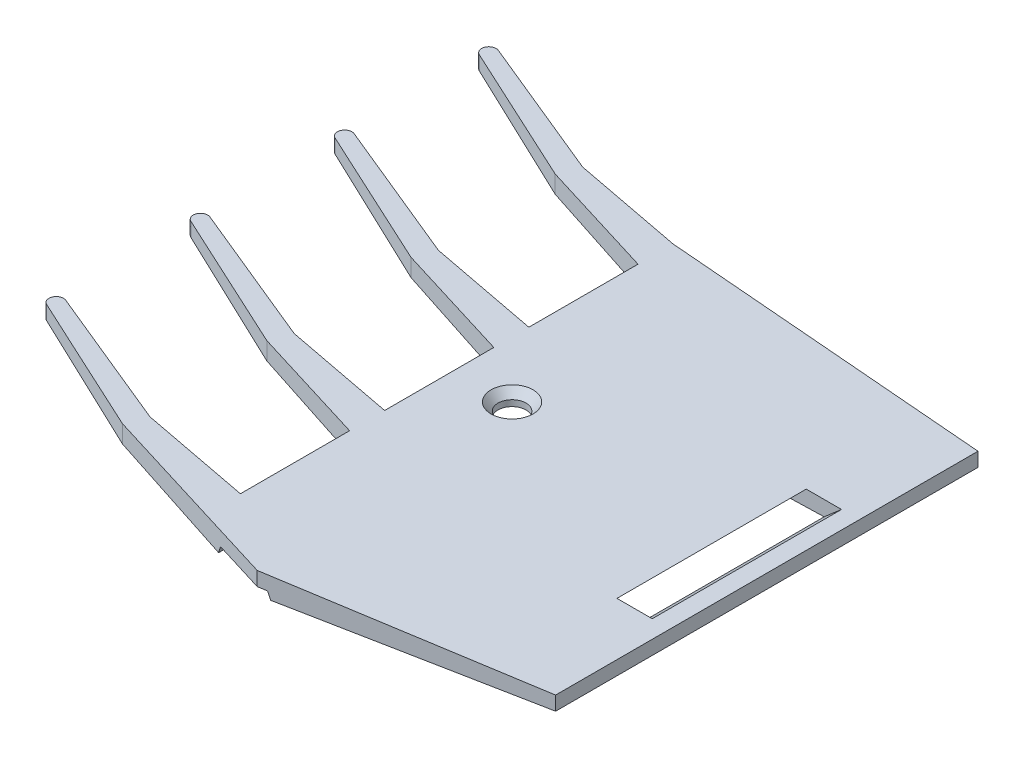
SolidWorks part; units mm, degrees
ref_plane "Front Plane" through (0, 0, 0) normal (0, 0, 1) x (1, 0, 0)
ref_plane "Top Plane" through (0, 0, 0) normal (0, 1, 0) x (1, 0, 0)
ref_plane "Right Plane" through (0, 0, 0) normal (1, 0, 0) x (0, 0, -1)
sketch "Sketch1" plane through (0, 0, 0) normal (0, 1, 0) x (1, 0, 0)
  line L0 (0, 0) -> (0, 69.8189) construction
  line L1 (-48.8454, 69.8189) -> (36.6825, 69.8189) construction
  line L2 (-48.8454, 69.8189) -> (-48.8454, -12) construction
  line L3 (-48.8454, -12) -> (36.6825, -12) construction
  line L4 (36.6825, 69.8189) -> (36.6825, -12) construction
  line L5 (0, 0) -> (36.6825, 0) construction
  line L6 (-48.8454, 69.8189) -> (-48.8454, -16) construction
  line L8 (-10.6742, 69.8189) -> (-48.8454, 69.8189) construction
  line L9 (-10.6742, -12) -> (-10.6742, 69.8189) construction
  line L10 (-27.7186, -3.4921) -> (0, -12) construction
  line L11 (-48.8454, 6.2826) -> (-27.7186, -3.4921) construction
  line L12 (-47.9432, 8.0952) -> (-48.8454, 6.2826) construction
  line L13 (-26.6234, -0.673) -> (-47.9432, 8.0952) construction
  line L14 (-10.6742, -3.7237) -> (-26.6234, -0.673) construction
  line L15 (-10.6742, 11.8509) -> (-10.6742, -3.7237) construction
  line L16 (-10.6742, 11.8509) -> (-27.7186, 17.0824) construction
  line L17 (-27.7186, 17.0824) -> (-48.8454, 26.8571) construction
  line L18 (-48.8454, 26.8571) -> (-47.9432, 28.6698) construction
  line L19 (-47.9432, 28.6698) -> (-26.6234, 19.9015) construction
  line L20 (-26.6234, 19.9015) -> (-10.6742, 16.8509) construction
  line L21 (-10.6742, 32.4254) -> (-10.6742, 16.8509) construction
  line L22 (-10.6742, 32.4254) -> (-27.7186, 37.657) construction
  line L23 (-27.7186, 37.657) -> (-48.8454, 47.4317) construction
  line L24 (-48.8454, 47.4317) -> (-47.9432, 49.2443) construction
  line L25 (-47.9432, 49.2443) -> (-26.6234, 40.4761) construction
  line L26 (-26.6234, 40.4761) -> (-10.6742, 37.4254) construction
  line L27 (-10.6742, 53) -> (-10.6742, 37.4254) construction
  line L28 (-10.6742, 53) -> (-27.7186, 58.2316) construction
  line L29 (-27.7186, 58.2316) -> (-48.8454, 68.0063) construction
  line L30 (-48.8454, 68.0063) -> (-47.9432, 69.8189) construction
  line L31 (-47.9432, 69.8189) -> (-26.6234, 61.0506) construction
  line L32 (-26.6234, 61.0506) -> (-10.6742, 58) construction
  line L33 (-27.7186, -3.4921) -> (0, -12)
  line L34 (-48.8454, 6.2826) -> (-27.7186, -3.4921) construction
  line L35 (-47.9432, 8.0952) -> (-48.8454, 6.2826) construction
  line L36 (-26.6234, -0.673) -> (-47.9432, 8.0952) construction
  line L37 (-10.6742, -3.7237) -> (-26.6234, -0.673)
  line L38 (-10.6742, 11.8509) -> (-10.6742, -3.7237)
  line L39 (-10.6742, 11.8509) -> (-27.7186, 17.0824)
  line L40 (-27.7186, 17.0824) -> (-48.8454, 26.8571) construction
  line L41 (-48.8454, 26.8571) -> (-47.9432, 28.6698) construction
  line L42 (-47.9432, 28.6698) -> (-26.6234, 19.9015) construction
  line L43 (-26.6234, 19.9015) -> (-10.6742, 16.8509)
  line L44 (-10.6742, 32.4254) -> (-10.6742, 16.8509)
  line L45 (-10.6742, 32.4254) -> (-27.7186, 37.657)
  line L46 (-27.7186, 37.657) -> (-48.8454, 47.4317) construction
  line L47 (-48.8454, 47.4317) -> (-47.9432, 49.2443) construction
  line L48 (-47.9432, 49.2443) -> (-26.6234, 40.4761) construction
  line L49 (-26.6234, 40.4761) -> (-10.6742, 37.4254)
  line L50 (-10.6742, 53) -> (-10.6742, 37.4254)
  line L51 (-10.6742, 53) -> (-27.7186, 58.2316)
  line L52 (-27.7186, 58.2316) -> (-48.8454, 68.0063) construction
  line L53 (-48.8454, 68.0063) -> (-47.9432, 69.8189) construction
  line L54 (-47.9432, 69.8189) -> (-26.6234, 61.0506) construction
  line L55 (-26.6234, 61.0506) -> (-10.6742, 58)
  line L56 (-26.6234, 61.0506) -> (-47.0538, 69.4531)
  line L57 (-27.7186, 58.2316) -> (-47.8806, 67.5599)
  line L58 (-47.0538, 48.8785) -> (-26.6234, 40.4761)
  line L59 (-27.7186, 37.657) -> (-47.8806, 46.9853)
  line L60 (-47.0538, 28.304) -> (-26.6234, 19.9015)
  line L61 (-27.7186, 17.0824) -> (-47.8806, 26.4108)
  line L62 (-47.0538, 7.7294) -> (-26.6234, -0.673)
  line L63 (-27.7186, -3.4921) -> (-47.8806, 5.8362)
  line L64 (33.3807, 69.8189) -> (33.3807, -12) construction
  line L65 (33.3807, 54.1459) -> (36.6825, 54.1459) construction
  line L67 (33.3807, -6.1144) -> (36.6825, -6.1144) construction
  line L72 (36.6825, 54.1459) -> (36.6825, -6.1144)
  line L73 (36.6825, -6.1144) -> (0, -12)
  line L74 (36.6825, 54.1459) -> (-10.6742, 58)
  arc A0 (-47.0538, 69.4531) -> (-47.8806, 67.5599) centre (-47.4468, 68.4976) ccw
  arc A1 (-47.0538, 48.8785) -> (-47.8806, 46.9853) centre (-47.4468, 47.923) ccw
  arc A2 (-47.0538, 28.304) -> (-47.8806, 26.4108) centre (-47.4468, 27.3484) ccw
  arc A3 (-47.0538, 7.7294) -> (-47.8806, 5.8362) centre (-47.4468, 6.7739) ccw
sketch "Sketch2" plane through (0, 0, 0) normal (0, 0, 1) x (1, 0, 0)
  line L0 (-47.9432, -2) -> (-7.9432, -3) construction
  line L1 (-7.9432, -3) -> (-7.5698, -2) construction
  line L2 (1.2804, -2) -> (-7.5698, -2) construction
  line L3 (1.2804, -2) -> (1.6538, -3) construction
  line L4 (1.6538, -3) -> (36.6825, -2) construction
  line L5 (36.6825, 0) -> (36.6825, -2) construction
  line L6 (36.6825, 0) -> (-47.9432, 0) construction
  line L8 (-48.8454, -1.9774) -> (-7.9432, -3)
  line L9 (-7.9432, -3) -> (-7.5698, -2)
  line L10 (1.2804, -2) -> (-7.5698, -2)
  line L11 (1.2804, -2) -> (1.6538, -3)
  line L12 (1.6538, -3) -> (36.6825, -2)
  line L13 (36.6825, 0) -> (36.6825, -2)
  line L14 (36.6825, 0) -> (-48.8454, 0)
  line L15 (-48.8454, 0) -> (-48.8454, -1.9774)
extrude "Boss-Extrude1" add sketch "Sketch2" against normal up to vertex (69.8189 mm away) from vertex at 12 starting at point (-48.8454, 0, 12)
extrude "Cut-Extrude1" cut sketch "Sketch1" against normal through all flip side to cut
sketch "Sketch3" plane through (0, 0, 0) normal (0, 0, 1) x (1, 0, 0)
  line L0 (34.1438, 0) -> (29.1134, 0)
  line L1 (29.1134, 0) -> (26.3323, -2.2955)
  line L2 (26.3323, -2.2955) -> (31.6731, -2.143)
  line L3 (31.6731, -2.143) -> (34.1438, 0)
  line L4 (36.6825, 0) -> (-47.9432, 0) construction
  line L5 (1.6538, -3) -> (36.6825, -2) construction
  line L6 (33.3807, 0) -> (30.884, -2.1655) construction
  line L7 (27.7228, -1.1477) -> (28.4989, -1.1365) construction
  line L8 (40.4025, 6.0903) -> (-28.0502, -53.2825) construction
  line L9 (27.122, -2.2729) -> (29.8758, 0) construction
  line L10 (7.4456, -18.5133) -> (39.1081, 7.6201) construction
  line L12 (32.9085, -1.0715) -> (32.1324, -1.0828) construction
  dimension "D1" = 0.5
extrude "Cut-Extrude2" cut sketch "Sketch3" against normal up to vertex from vertex
sketch "Sketch4" plane through (0, 0, 0) normal (0, 1, 0) x (1, 0, 0)
  circle A0 centre (-2.6447, 27) radius 2.9924 construction
  circle A1 centre (-2.6447, 27) radius 2.9924
extrude "Cut-Extrude3" cut sketch "Sketch4" against normal through all draft 41
sketch "Sketch5" plane through (0, 0, 0) normal (0, 1, 0) x (1, 0, 0)
  circle A0 centre (-2.6447, 27) radius 1.5 construction
  circle A1 centre (-2.6447, 27) radius 1.5 construction
  circle A2 centre (-2.6447, 27) radius 2
  dimension "D1" = 4
extrude "Cut-Extrude4" cut sketch "Sketch5" against normal through all
